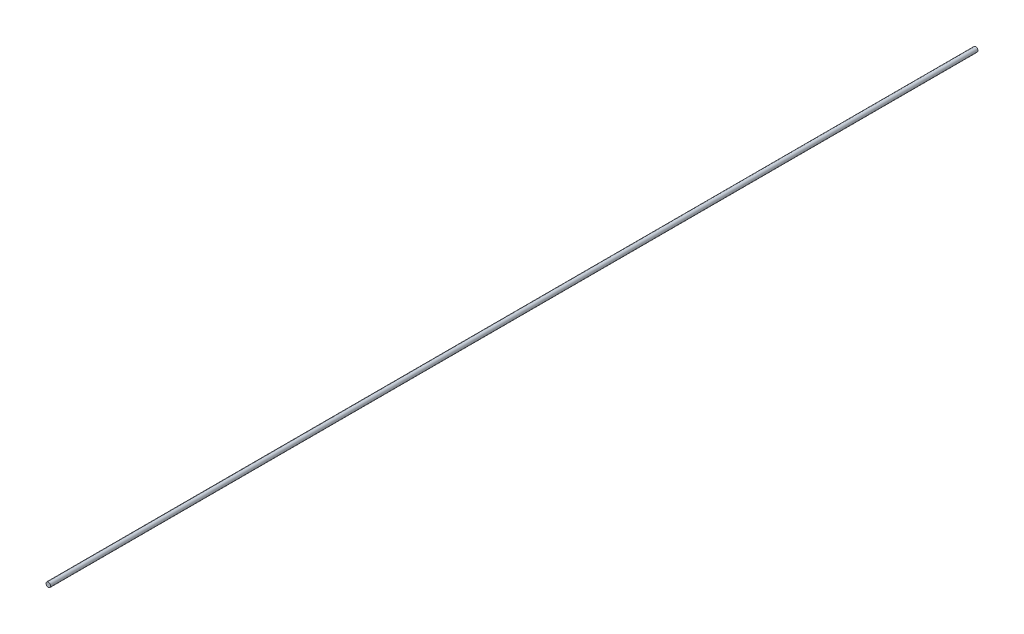
SolidWorks part; units mm, degrees
ref_plane "Front Plane" through (0, 0, 0) normal (0, 0, 1) x (1, 0, 0)
ref_plane "Top Plane" through (0, 0, 0) normal (0, 1, 0) x (1, 0, 0)
ref_plane "Right Plane" through (0, 0, 0) normal (1, 0, 0) x (0, 0, -1)
sketch "Sketch1" plane through (0, 0, 0) normal (0, 0, 1) x (1, 0, 0)
  circle A0 centre (0, 0) radius 1
  dimension "D1" = 2
extrude "Boss-Extrude1" add sketch "Sketch1" along normal blind 400
